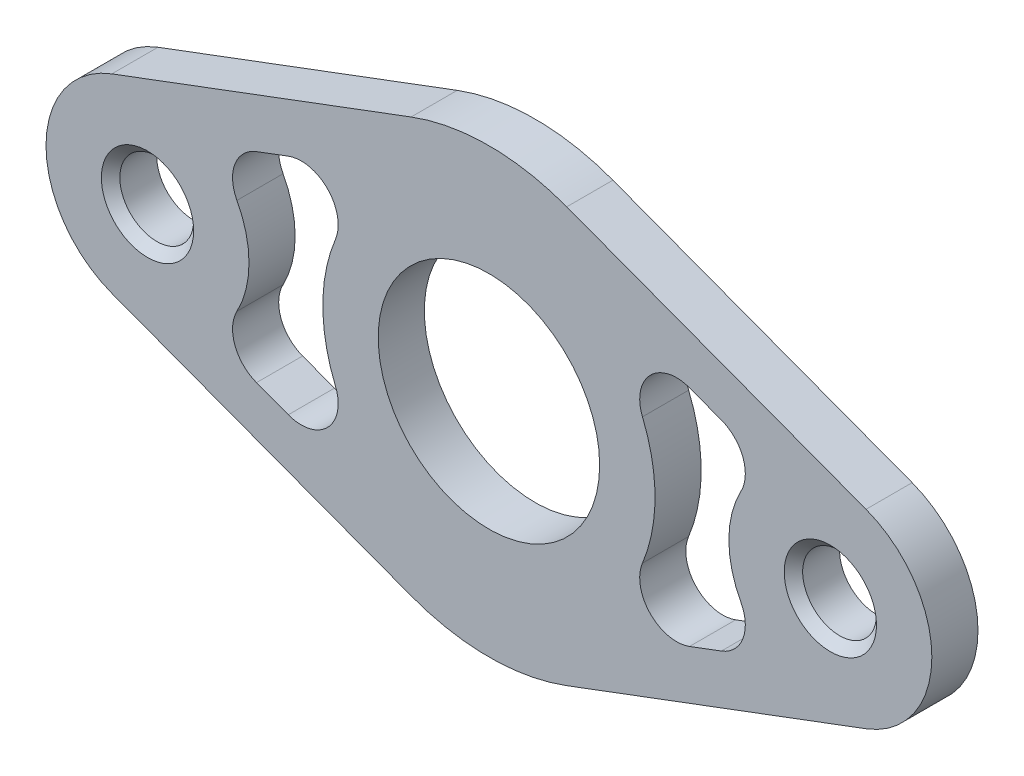
SolidWorks part; units mm, degrees
material "AISI 1020"
ref_plane "Front Plane" through (0, 0, 0) normal (0, 0, 1) x (1, 0, 0)
ref_plane "Top Plane" through (0, 0, 0) normal (0, 1, 0) x (1, 0, 0)
ref_plane "Right Plane" through (0, 0, 0) normal (1, 0, 0) x (0, 0, -1)
sketch "Sketch1" plane through (0, 0, 0) normal (0, 0, 1) x (1, 0, 0)
  line L0 (-40.8649, 10.2987) -> (-8.4324, 22.4698)
  line L1 (0, 11.9616) -> (0, 0) construction
  line L2 (0, 0) -> (8.8946, 0) construction
  line L3 (-40.8649, -10.2987) -> (-8.4324, -22.4698)
  line L4 (40.8649, -10.2987) -> (8.4324, -22.4698)
  line L5 (40.8649, 10.2987) -> (8.4324, 22.4698)
  arc A0 (-8.4324, -22.4698) -> (8.4324, -22.4698) centre (0, 0) ccw
  circle A1 centre (-37, 0) radius 4
  arc A2 (-40.8649, 10.2987) -> (-40.8649, -10.2987) centre (-37, 0) ccw
  arc A3 (40.8649, 10.2987) -> (40.8649, -10.2987) centre (37, 0) cw
  circle A4 centre (37, 0) radius 4
  arc A5 (8.4324, 22.4698) -> (-8.4324, 22.4698) centre (0, 0) ccw
  arc A10 (40.8649, -10.2987) -> (40.8649, 10.2987) centre (37, 0) ccw
  circle A15 centre (0, 0) radius 12
  dimension "D1" = 48
  dimension "D2" = 8
  dimension "D3" = 37
  dimension "D4" = 22
  dimension "D5" = 24
extrude "Boss-Extrude1" add sketch "Sketch1" along normal blind 5 contours L5 A5 L0 A2 L3 A0 L4 A3 A4 A1
sketch "Sketch2" plane through (0, 0, 5) normal (0, 0, 1) x (1, 0, 0)
  line L1 (21.7431, 12.1342) -> (25.1898, 10.8407)
  line L2 (21.7431, -12.1342) -> (25.1898, -10.8407)
  line L4 (40.8649, -10.2987) -> (8.4324, -22.4698) construction
  line L5 (40.8649, 10.2987) -> (8.4324, 22.4698) construction
  line L6 (0, 0) -> (0, 9.2662) construction
  line L7 (-21.7431, -12.1342) -> (-25.1898, -10.8407)
  line L8 (-21.7431, 12.1342) -> (-25.1898, 10.8407)
  arc A0 (16.6399, -6.8639) -> (16.6399, 6.8639) centre (0, 0) ccw
  arc A1 (27.3086, 5.2035) -> (27.3086, -5.2035) centre (37, 0) ccw
  arc A2 (21.7431, 12.1342) -> (16.6399, 6.8639) centre (20.3377, 8.3892) ccw
  arc A3 (25.1898, 10.8407) -> (27.3086, 5.2035) centre (23.7844, 7.0957) cw
  arc A4 (25.1898, -10.8407) -> (27.3086, -5.2035) centre (23.7844, -7.0957) ccw
  arc A5 (21.7431, -12.1342) -> (16.6399, -6.8639) centre (20.3377, -8.3892) cw
  arc A6 (-21.7431, -12.1342) -> (-16.6399, -6.8639) centre (-20.3377, -8.3892) ccw
  arc A7 (-25.1898, -10.8407) -> (-27.3086, -5.2035) centre (-23.7844, -7.0957) cw
  arc A8 (-25.1898, 10.8407) -> (-27.3086, 5.2035) centre (-23.7844, 7.0957) ccw
  arc A9 (-21.7431, 12.1342) -> (-16.6399, 6.8639) centre (-20.3377, 8.3892) cw
  arc A10 (-27.3086, 5.2035) -> (-27.3086, -5.2035) centre (-37, 0) cw
  arc A11 (-16.6399, -6.8639) -> (-16.6399, 6.8639) centre (0, 0) cw
  dimension "D1" = 36
  dimension "D2" = 22
  dimension "D3" = 4
  dimension "D4" = 5
  dimension "D5" = 5
extrude "Cut-Extrude1" cut sketch "Sketch2" against normal up to next contours A10 A7 L7 A6 A11 A9 L8 A8
chamfer "Chamfer1" distance 1 angle 45 2 edges at (41, 0, 5) (-33, 0, 5)
